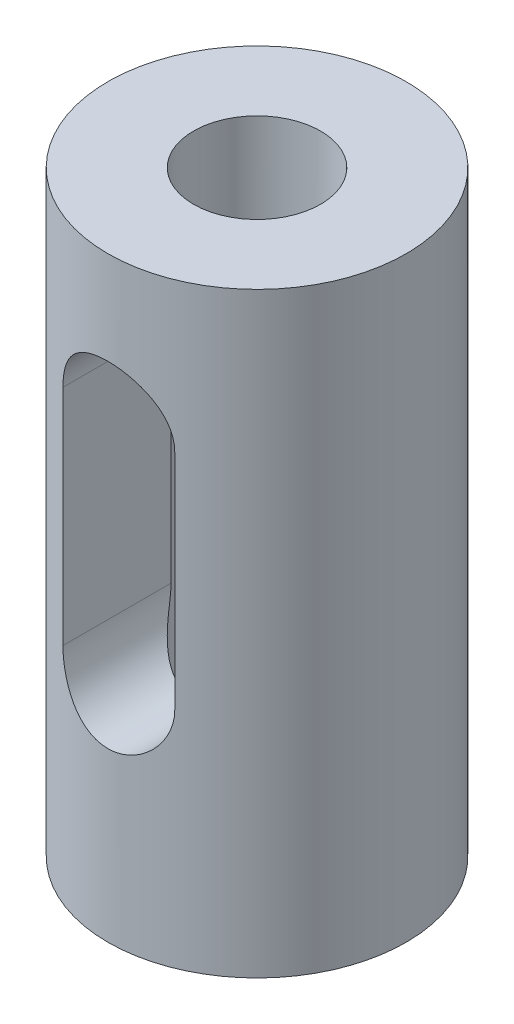
SolidWorks part; units mm, degrees
ref_plane "Front Plane" through (0, 0, 0) normal (0, 0, 1) x (1, 0, 0)
ref_plane "Top Plane" through (0, 0, 0) normal (0, 1, 0) x (1, 0, 0)
ref_plane "Right Plane" through (0, 0, 0) normal (1, 0, 0) x (0, 0, -1)
sketch "Sketch1" plane through (0, 0, 0) normal (0, 1, 0) x (1, 0, 0)
  circle A0 centre (0, 0) radius 3.175
  dimension "D1" = 6.35
extrude "Boss-Extrude1" add sketch "Sketch1" along normal blind 12.7
hole_wizard "Tap Drill for #6-32 Tap1" positions "Sketch3" profile "Sketch2" hole size "#6-32" standard "ANSI Inch" end condition through all
sketch "Sketch3" plane through (0, 12.7, 0) normal (0, 1, 0) x (1, 0, 0)
  point P0 (0, 0)
sketch "Sketch2" plane through (0, 12.7, 0) normal (1, 0, 0) x (0, 0, 1)
  line L0 (0, 0) -> (0, 12.7)
  line L1 (0, 12.7) -> (1.3525, 12.7)
  line L2 (1.3525, 12.7) -> (1.3525, 0)
  line L5 (1.3525, 0) -> (0, 0)
  line L11 (0, -6.35) -> (0, 107.95) construction
  dimension "Thru Hole Dia." = 2.7051
  dimension "Thru Hole Depth" = 12.7
cosmetic thread "Cosmetic Thread1" parameters "D2"=3.5052
cosmetic thread "Cosmetic Thread2" parameters "D2"=3.5052
sketch "Sketch4" plane through (0, 0, 0) normal (0, 0, 1) x (1, 0, 0)
  line L0 (0, 9.525) -> (0, 4.7625) construction
  line L1 (1.1906, 9.525) -> (1.1906, 4.7625)
  line L2 (-1.1906, 9.525) -> (-1.1906, 4.7625)
  line L3 (-3.175, 0) -> (3.175, 0) construction
  line L4 (3.175, 12.7) -> (-3.175, 12.7) construction
  arc A0 (1.1906, 9.525) -> (-1.1906, 9.525) centre (0, 9.525) ccw
  arc A1 (-1.1906, 4.7625) -> (1.1906, 4.7625) centre (0, 4.7625) ccw
  point P3 (0, 7.1437)
  dimension "D1" = 2.3813
  dimension "D2" = 4.7625
  dimension "D3" = 3.175
extrude "Cut-Extrude1" cut sketch "Sketch4" against normal through all both and the other way through all
